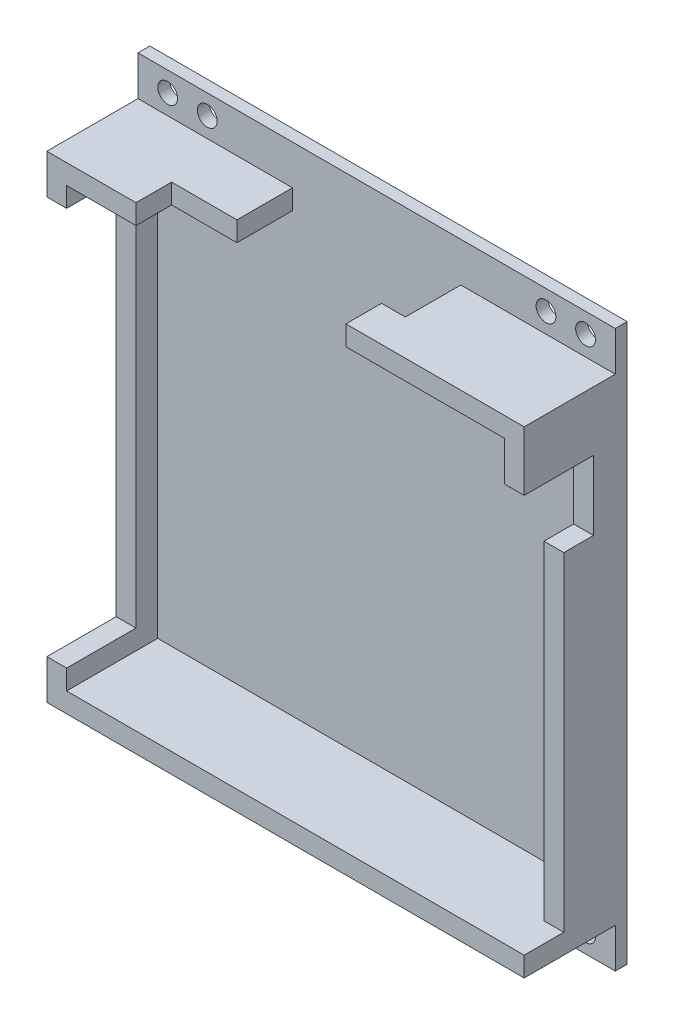
SolidWorks part; units mm, degrees
ref_plane "Front Plane" through (0, 0, 0) normal (0, 0, 1) x (1, 0, 0)
ref_plane "Top Plane" through (0, 0, 0) normal (0, 1, 0) x (1, 0, 0)
ref_plane "Right Plane" through (0, 0, 0) normal (1, 0, 0) x (0, 0, -1)
sketch "Sketch1" plane through (0, 0, 0) normal (0, 0, 1) x (1, 0, 0)
  line L1 (-55.25, -55.25) -> (55.25, -55.25)
  line L2 (-55.25, -55.25) -> (-55.25, 55.25)
  line L3 (-55.25, 55.25) -> (55.25, 55.25)
  line L4 (55.25, -55.25) -> (55.25, 55.25)
  line L5 (-55.25, -55.25) -> (55.25, 55.25) construction
  line L6 (-55.25, 55.25) -> (55.25, -55.25) construction
  line L7 (-60.25, -60.25) -> (60.25, -60.25)
  line L8 (-60.25, -60.25) -> (-60.25, 60.25)
  line L9 (-60.25, 60.25) -> (60.25, 60.25)
  line L10 (60.25, -60.25) -> (60.25, 60.25)
  line L11 (-60.25, -60.25) -> (60.25, 60.25) construction
  line L12 (-60.25, 60.25) -> (60.25, -60.25) construction
  point P0 (0, 0)
  point P6 (0, 0)
  dimension "D1" = 110.5
  dimension "D2" = 110.5
  dimension "D3" = 5
extrude "Boss-Extrude1" add sketch "Sketch1" along normal blind 23
sketch "Sketch2" plane through (0, 0, 0) normal (0, 0, -1) x (-1, 0, 0)
  line L1 (-60.25, -60.25) -> (60.25, -60.25)
  line L2 (-60.25, -60.25) -> (-60.25, 60.25)
  line L3 (-60.25, 60.25) -> (60.25, 60.25)
  line L4 (60.25, -60.25) -> (60.25, 60.25)
  line L5 (-60.25, -60.25) -> (60.25, 60.25) construction
  line L6 (-60.25, 60.25) -> (60.25, -60.25) construction
  point P0 (0, 0)
extrude "Boss-Extrude2" add sketch "Sketch2" along normal blind 3
sketch "Sketch3" plane through (-55.25, 0, 0) normal (1, 0, 0) x (0, 0, -1)
  line L0 (-23, 50.25) -> (-5.5, 50.25)
  line L2 (-23, 55.25) -> (-23, -55.25) construction
  line L4 (-5.5, 50.25) -> (-5.5, -50.25)
  line L5 (-5.5, -50.25) -> (-23, -50.25)
  line L6 (-23, 50.25) -> (-23, -50.25)
  line L7 (-23, 55.25) -> (0, 55.25) construction
  line L8 (-23, -55.25) -> (0, -55.25) construction
  dimension "D1" = 5
  dimension "D2" = 17.5
  dimension "D3" = 5
extrude "Cut-Extrude1" cut sketch "Sketch3" against normal blind 47 contours L6 L5 L4 L0
sketch "Sketch5" plane through (0, 55.25, 0) normal (0, -1, 0) x (1, 0, 0)
  line L0 (-37.75, 23) -> (-37.75, 14)
  line L1 (55.25, 23) -> (-55.25, 23) construction
  line L2 (-37.75, 14) -> (-21.25, 14)
  line L3 (15.25, 14) -> (15.25, 23)
  line L4 (15.25, 23) -> (-37.75, 23)
  line L5 (-55.25, 23) -> (-55.25, 0) construction
  line L6 (55.25, 23) -> (55.25, 0) construction
  line L7 (21.25, 14) -> (21.25, 0)
  line L8 (55.25, 0) -> (-55.25, 0) construction
  line L9 (21.25, 0) -> (-21.25, 0)
  line L10 (-21.25, 0) -> (-21.25, 14)
  line L11 (15.25, 14) -> (21.25, 14)
  dimension "D1" = 17.5
  dimension "D2" = 40
  dimension "D3" = 9
  dimension "D4" = 34
  dimension "D5" = 34
extrude "Cut-Extrude2" cut sketch "Sketch5" against normal blind 47
sketch "Sketch6" plane through (55.25, 0, 0) normal (-1, 0, 0) x (0, 0, 1)
  line L0 (23, 45.25) -> (5.5, 45.25)
  line L1 (23, -55.25) -> (23, 55.25) construction
  line L2 (5.5, 45.25) -> (5.5, 27.75)
  line L3 (5.5, 27.75) -> (13, 27.75)
  line L4 (13, 27.75) -> (13, -55.25)
  line L5 (23, -55.25) -> (0, -55.25) construction
  line L6 (13, -55.25) -> (23, -55.25)
  line L7 (23, -55.25) -> (23, 45.25)
  line L8 (23, 55.25) -> (0, 55.25) construction
  dimension "D1" = 10
  dimension "D2" = 17.5
  dimension "D3" = 17.5
  dimension "D4" = 10
extrude "Cut-Extrude3" cut sketch "Sketch6" against normal blind 47
sketch "Sketch7" plane through (0, 0, -3) normal (0, 0, -1) x (-1, 0, 0)
  line L0 (-60.25, 60.25) -> (-60.25, 70.25)
  line L1 (-60.25, 70.25) -> (60.25, 70.25)
  line L2 (60.25, 70.25) -> (60.25, 60.25)
  line L3 (60.25, 60.25) -> (-60.25, 60.25)
  line L4 (-60.25, -60.25) -> (-60.25, -70.25)
  line L5 (-60.25, -70.25) -> (60.25, -70.25)
  line L6 (60.25, -70.25) -> (60.25, -60.25)
  line L7 (60.25, -60.25) -> (-60.25, -60.25)
  circle A0 centre (-52.75, 65.25) radius 2.5
  circle A1 centre (-42.75, 65.25) radius 2.5
  circle A2 centre (52.75, 65.25) radius 2.5
  circle A3 centre (42.75, 65.25) radius 2.5
  circle A4 centre (-52.75, -65.25) radius 2.5
  circle A5 centre (-42.75, -65.25) radius 2.5
  circle A6 centre (42.75, -65.25) radius 2.5
  circle A7 centre (52.75, -65.25) radius 2.5
  dimension "D2" = 5
  dimension "D3" = 5
  dimension "D4" = 5
  dimension "D5" = 5
  dimension "D7" = 10
  dimension "D9" = 10
  dimension "D11" = 5
  dimension "D12" = 5
  dimension "D13" = 5
  dimension "D17" = 5
  dimension "D18" = 5
  dimension "D19" = 5
  dimension "D20" = 5
  dimension "D22" = 10
  dimension "D23" = 5
  dimension "D24" = 5
  dimension "D25" = 5
  dimension "D26" = 5
  dimension "D1" = 10
  dimension "D6" = 7.5
  dimension "D8" = 7.5
  dimension "D10" = 5
  dimension "D14" = 10
  dimension "D15" = 7.5
  dimension "D16" = 10
  dimension "D21" = 7.5
extrude "Boss-Extrude3" add sketch "Sketch7" against normal blind 3
